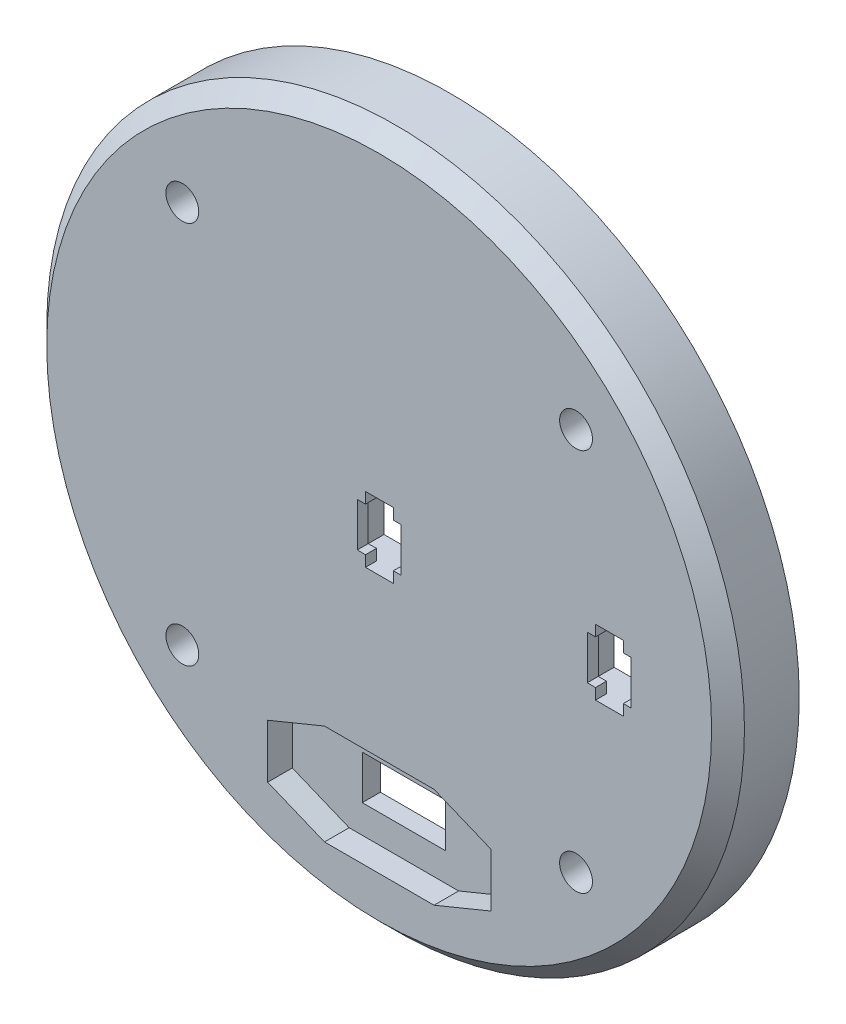
SolidWorks part; units mm, degrees
ref_plane "Front Plane" through (0, 0, 0) normal (0, 0, 1) x (1, 0, 0)
ref_plane "Top Plane" through (0, 0, 0) normal (0, 1, 0) x (1, 0, 0)
ref_plane "Right Plane" through (0, 0, 0) normal (1, 0, 0) x (0, 0, -1)
ref_plane "Plane1" through (0, 0, -25.5) normal (0, 0, 1) x (1, 0, 0)
sketch "Sketch2" plane through (0, 0, -25.5) normal (0, 0, 1) x (1, 0, 0)
  circle A0 centre (0, 0) radius 32 construction
  circle A1 centre (0, 0) radius 31.85
  dimension "D1" = 64
  dimension "D2" = 0.15
extrude "Boss-Extrude1" add sketch "Sketch2" against normal blind 6.5
sketch "Sketch3" plane through (0, 0, -32) normal (0, 0, -1) x (-1, 0, 0)
  line L0 (-18, 3) -> (-24, 3)
  line L1 (3, 3) -> (-3, 3)
  line L2 (3, 3) -> (3, -3)
  line L3 (3, -3) -> (-3, -3)
  line L4 (-3, 3) -> (-3, -3)
  line L5 (3, 3) -> (-3, -3) construction
  line L6 (3, -3) -> (-3, 3) construction
  line L7 (-18, 3) -> (-18, -3)
  line L8 (-18, -3) -> (-24, -3)
  line L9 (-24, 3) -> (-24, -3)
  line L10 (-18, 3) -> (-24, -3) construction
  line L11 (-18, -3) -> (-24, 3) construction
  point P0 (0, 0)
  point P7 (-21, 0)
  dimension "D1" = 6
  dimension "D2" = 6
  dimension "D4" = 21
  dimension "D3" = 2
extrude "Cut-Extrude1" cut sketch "Sketch3" against normal blind 6.5
chamfer "Chamfer1" distance 6 angle 27 8 edges at (3, 0, -32) (0, -3, -32) (-3, 0, -32) (0, 3, -32) (18, 0, -32) (21, 3, -32) (24, 0, -32) (21, -3, -32)
sketch "Sketch5" plane through (0, 0, 0) normal (0, 0, 1) x (1, 0, 0)
  line L0 (0, -31.6068) -> (0, 32) construction
  line L2 (-31.85, 0) -> (31.85, 0) construction
  circle A0 centre (-17.9719, -17.5002) radius 1.5
  arc A1 (28.3907, 14.7638) -> (-28.3907, 14.7638) centre (0, 0) ccw construction
  circle A2 centre (0, 0) radius 31.85 construction
  circle A3 centre (17.9719, -17.5002) radius 1.5
  circle A4 centre (17.9719, 17.5002) radius 1.5
  circle A5 centre (-17.9719, 17.5002) radius 1.5
extrude "Cut-Extrude2" cut sketch "Sketch5" against normal through all
sketch "Sketch6" plane through (0, 0, -32) normal (0, 0, 1) x (1, 0, 0)
  line L0 (0, -32) -> (0, 31.85) construction
  line L2 (-32, 0) -> (31.85, 0) construction
  circle A0 centre (-17.9719, -17.5002) radius 3
  arc A1 (-28.3907, -14.7638) -> (28.3907, -14.7638) centre (0, 0) ccw construction
  arc A3 (-28.3907, 14.7638) -> (-28.3907, -14.7638) centre (0, 0) ccw construction
  circle A4 centre (0, 0) radius 31.85 construction
  circle A5 centre (17.9719, -17.5002) radius 3
  circle A6 centre (17.9719, 17.5002) radius 3
  circle A7 centre (-17.9719, 17.5002) radius 3
  dimension "D1" = 6
extrude "Cut-Extrude3" cut sketch "Sketch6" along normal blind 3
chamfer "Chamfer3" distance 1.5 angle 45 1 edges at (31.85, 0, -25.5)
sketch "Sketch7" plane through (0, 0, -25.5) normal (0, 0, 1) x (1, 0, 0)
  line L0 (0, 0) -> (21.0054, 0) construction
  line L1 (10.5027, 0) -> (10.5027, 9.0294) construction
  line L2 (-2, -2) -> (-2, 2)
  line L3 (-3, -3) -> (3, -3) construction
  line L4 (-3, -3) -> (-3, 3)
  line L5 (-3, 3) -> (3, 3) construction
  line L6 (3, -3) -> (3, 3)
  line L7 (-3, -3) -> (3, 3) construction
  line L8 (-3, 3) -> (3, -3) construction
  line L9 (-2, 2) -> (2, 2) construction
  line L10 (2, -2) -> (2, 2)
  line L11 (-2, -2) -> (2, -2) construction
  line L12 (-2, -2) -> (-1.25, -2)
  line L13 (-1.25, -2) -> (-1.25, -3)
  line L14 (0.0205, 0) -> (0.0205, -2.4966) construction
  line L15 (-1.25, 2) -> (-1.25, 3)
  line L16 (-2, 2) -> (-1.25, 2)
  line L17 (1.2909, -2) -> (1.2909, -3)
  line L18 (2.0409, -2) -> (1.2909, -2)
  line L19 (2.0409, 2) -> (1.2909, 2)
  line L20 (1.2909, 2) -> (1.2909, 3)
  line L21 (19, -2) -> (19, 2)
  line L22 (18, -3) -> (18, 3)
  line L23 (-1.25, -3) -> (-3, -3)
  line L24 (-1.25, 3) -> (-3, 3)
  line L25 (1.2909, 3) -> (3, 3)
  line L26 (1.2909, -3) -> (3, -3)
  line L27 (24, -3) -> (24, 3)
  line L28 (23, -2) -> (23, 2)
  line L29 (19, -2) -> (19.75, -2)
  line L30 (19.75, -2) -> (19.75, -3)
  line L31 (19.75, 2) -> (19.75, 3)
  line L32 (19, 2) -> (19.75, 2)
  line L33 (22.2909, -2) -> (22.2909, -3)
  line L34 (23.0409, -2) -> (22.2909, -2)
  line L35 (23.0409, 2) -> (22.2909, 2)
  line L36 (22.2909, 2) -> (22.2909, 3)
  line L37 (19.75, -3) -> (18, -3)
  line L38 (19.75, 3) -> (18, 3)
  line L39 (22.2909, 3) -> (24, 3)
  line L40 (22.2909, -3) -> (24, -3)
  line L41 (18, -3) -> (24, -3) construction
  line L42 (18, 3) -> (24, 3) construction
  line L43 (18, -3) -> (24, 3) construction
  line L44 (18, 3) -> (24, -3) construction
  line L45 (19, 2) -> (23, 2) construction
  line L46 (19, -2) -> (23, -2) construction
  line L47 (21.0205, 0) -> (21.0205, -2.4966) construction
  dimension "D2" = 0.75
  dimension "D1" = 1
  dimension "D3" = 2
extrude "Boss-Extrude2" add sketch "Sketch7" against normal blind 1
sketch "Sketch8" plane through (0, 0, 0) normal (0, 0, 1) x (1, 0, 0)
  line L1 (-10, 10) -> (10, 10)
  line L2 (-10, 10) -> (-10, -10)
  line L3 (-10, -10) -> (10, -10)
  line L4 (10, 10) -> (10, -10)
  line L5 (-10, 10) -> (10, -10) construction
  line L6 (-10, -10) -> (10, 10) construction
  circle A0 centre (0, 0) radius 38.5221
  point P0 (0, 0)
  dimension "D1" = 20
  dimension "D2" = 20
extrude "Cut-Extrude4" [suppressed] cut sketch "Sketch8" against normal through all
sketch "Sketch10" plane through (0, 0, -32) normal (0, 0, -1) x (-1, 0, 0)
  line L0 (3.2932, -22.0031) -> (-3.3068, -22.0031) construction
  line L1 (3.2932, -20.5031) -> (-3.3068, -20.5031) construction
  line L2 (3.2932, -20.5031) -> (3.2932, -23.5031) construction
  line L3 (3.2932, -23.5031) -> (-3.3068, -23.5031) construction
  line L4 (-3.3068, -20.5031) -> (-3.3068, -23.5031) construction
  line L5 (3.7932, -24.0031) -> (-3.8068, -24.0031)
  line L6 (-0.0068, -20.5031) -> (-0.0068, -23.5031) construction
  line L7 (-3.8068, -20.0031) -> (-3.8068, -24.0031)
  line L8 (3.7932, -20.0031) -> (-3.8068, -20.0031)
  line L9 (3.7932, -20.0031) -> (3.7932, -24.0031)
  point P8 (-0.0002, -21.9814)
  dimension "D1" = 6.6
  dimension "D2" = 3
  dimension "D3" = 0.5
extrude "Cut-Extrude5" cut sketch "Sketch10" against normal through all
sketch "Sketch11" plane through (0, 0, -25.5) normal (0, 0, 1) x (1, 0, 0)
  line L0 (0.0068, -24.0031) -> (0.0068, -20.0031) construction
  line L1 (3.8068, -24.0031) -> (-3.7932, -24.0031) construction
  line L2 (-3.7932, -20.0031) -> (3.8068, -20.0031) construction
  line L3 (-9.6796, -19.8874) -> (-9.6796, -24.1188) construction
  line L4 (-3.7932, -24.0031) -> (-3.7932, -20.0031) construction
  line L5 (-3.7932, -22.0031) -> (3.8068, -22.0031) construction
  line L6 (3.8068, -20.0031) -> (3.8068, -24.0031) construction
  line L7 (-3.7932, -22.0031) -> (-11.5985, -22.0031) construction
  line L8 (-4.8948, -26.084) -> (4.9085, -26.084) construction
  line L9 (-4.8948, -26.084) -> (-9.6796, -24.1188) construction
  line L10 (-4.8948, -17.9221) -> (4.9085, -17.9221) construction
  line L11 (-4.8948, -17.9221) -> (-9.6796, -19.8874) construction
  line L12 (4.9085, -17.9221) -> (9.6932, -19.8874) construction
  line L13 (9.6932, -19.8874) -> (9.6932, -24.1188) construction
  line L14 (4.9085, -26.084) -> (9.6932, -24.1188) construction
  line L15 (-4.9935, -17.4221) -> (5.0072, -17.4221)
  line L16 (5.0072, -17.4221) -> (10.1932, -19.5522)
  line L17 (10.1932, -19.5522) -> (10.1932, -24.4539)
  line L18 (5.0072, -26.584) -> (10.1932, -24.4539)
  line L19 (-4.9935, -26.584) -> (5.0072, -26.584)
  line L20 (-4.9935, -26.584) -> (-10.1796, -24.4539)
  line L21 (-10.1796, -19.5522) -> (-10.1796, -24.4539)
  line L22 (-4.9935, -17.4221) -> (-10.1796, -19.5522)
  point P15 (-9.6796, -22.0031)
  point P21 (0.0068, -17.9221)
  point P24 (0.0068, -26.084)
  dimension "D1" = 0.5
extrude "Cut-Extrude6" cut sketch "Sketch11" against normal blind 2.25
chamfer "Chamfer4" distance 4 angle 33 4 edges at (3.8068, -22.0031, -32) (0.0068, -24.0031, -32) (-3.7932, -22.0031, -32) (0.0068, -20.0031, -32)
